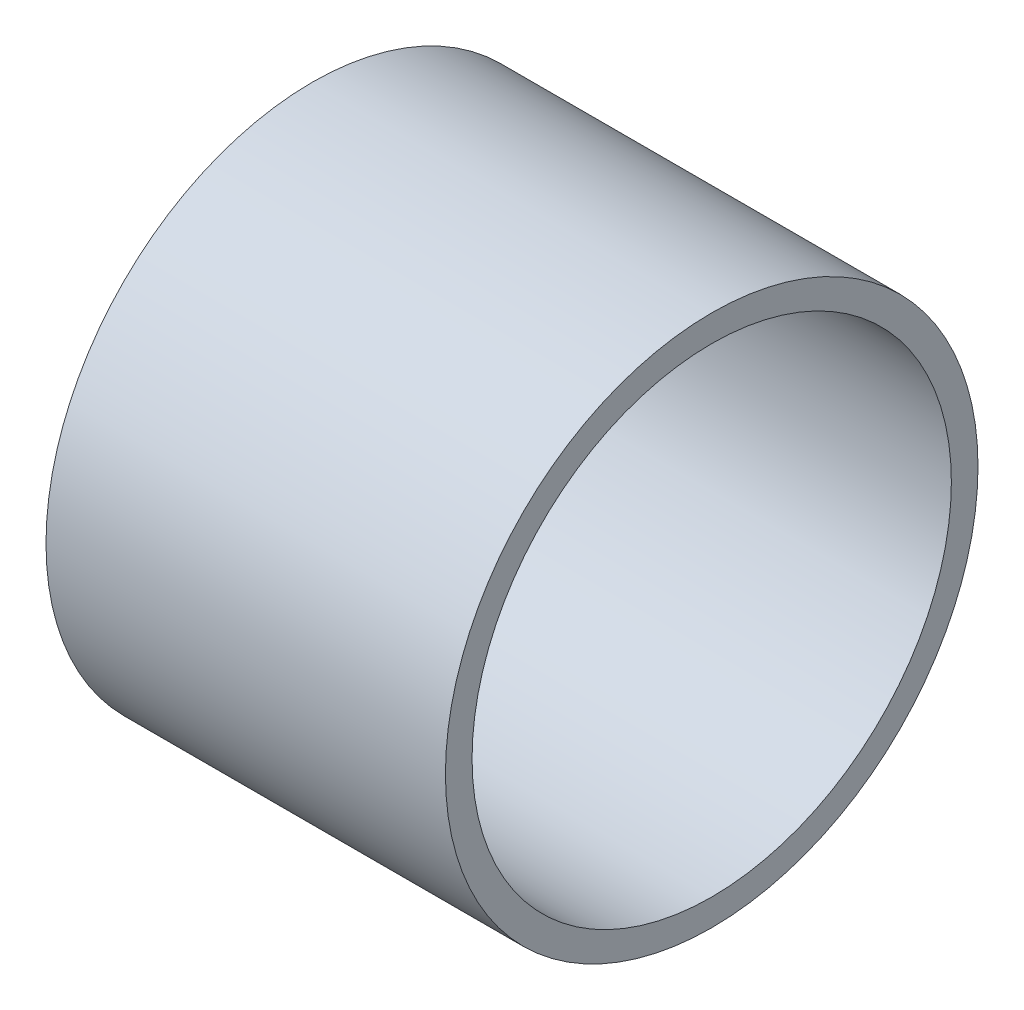
SolidWorks part; units mm, degrees
material "Laiton"
ref_plane "Plan de face" through (0, 0, 0) normal (0, 0, 1) x (1, 0, 0)
ref_plane "Plan de dessus" through (0, 0, 0) normal (0, 1, 0) x (1, 0, 0)
ref_plane "Plan de droite" through (0, 0, 0) normal (1, 0, 0) x (0, 0, -1)
ref_plane "Plan4" through (0, 0, 0) normal (0, 0, -1) x (-1, 0, 0)
sketch "Esquisse1" plane through (0, 0, 0) normal (0, 0, -1) x (-1, 0, 0)
  line L0 (-60, 40) -> (-60, 36)
  line L1 (-60, 36) -> (0, 36)
  line L2 (0, 36) -> (0, 40)
  line L3 (0, 40) -> (-60, 40)
  line L4 (-60, 0) -> (0, 0) construction
revolve "Révolution1" add sketch "Esquisse1" angle 360 about L4
